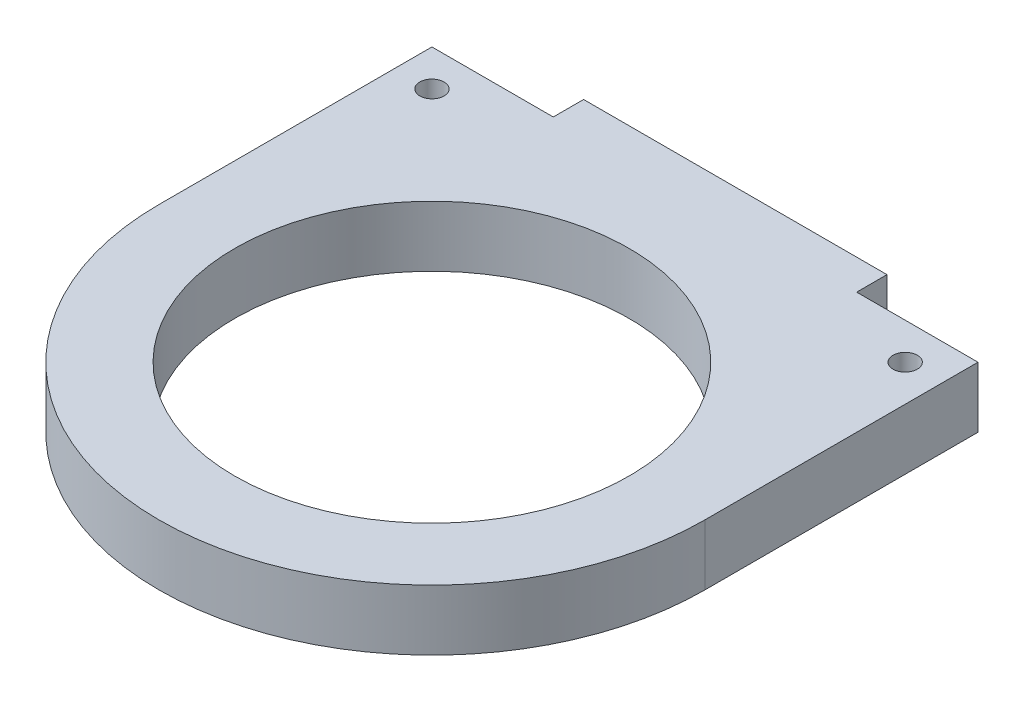
SolidWorks part; units mm, degrees
material "아크릴(내충격성)"
ref_plane "정면" through (0, 0, 0) normal (0, 0, 1) x (1, 0, 0)
ref_plane "윗면" through (0, 0, 0) normal (0, 1, 0) x (1, 0, 0)
ref_plane "우측면" through (0, 0, 0) normal (1, 0, 0) x (0, 0, -1)
sketch "스케치1" plane through (0, 0, 0) normal (0, 1, 0) x (1, 0, 0)
  line L0 (-25, 45) -> (-25, 50)
  line L1 (-45, 45) -> (-25, 45)
  line L2 (-45, 45) -> (-45, 0)
  line L4 (45, 45) -> (45, 0)
  line L5 (-45, 45) -> (45, -45) construction
  line L6 (-45, -45) -> (45, 45) construction
  line L7 (-25, 50) -> (25, 50)
  line L8 (25, 50) -> (25, 45)
  line L9 (25, 45) -> (45, 45)
  circle A0 centre (0, 0) radius 32.5
  arc A1 (-45, 0) -> (45, 0) centre (0, 0) ccw
  circle A2 centre (-39, 39) radius 2
  circle A3 centre (39, 39) radius 2
  dimension "D1" = 90
  dimension "D2" = 65
  dimension "D3" = 6
  dimension "D4" = 6
  dimension "D5" = 5
  dimension "D6" = 20
  dimension "D7" = 20
extrude "보스-돌출1" add sketch "스케치1" along normal blind 10
